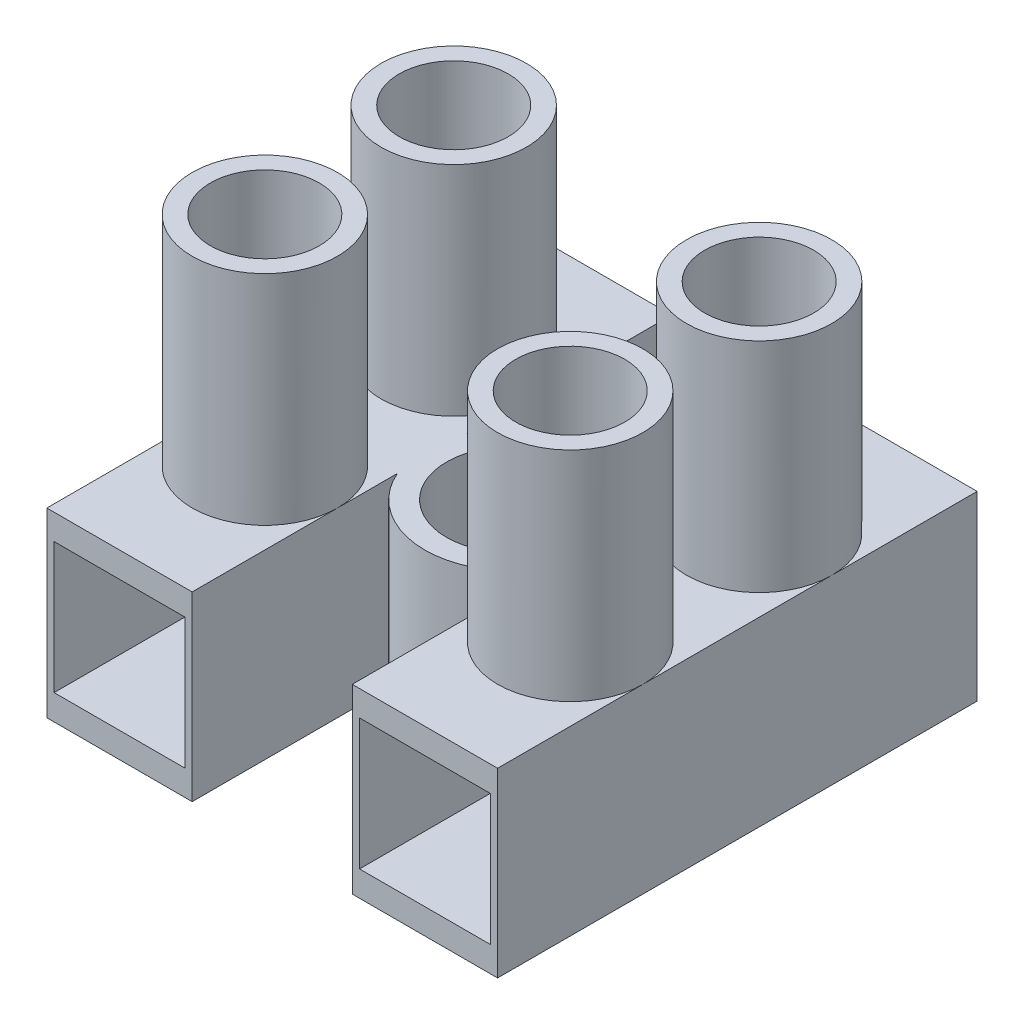
SolidWorks part; units mm, degrees
material "Nylon 6/10"
ref_plane "Front Plane" through (0, 0, 0) normal (0, 0, 1) x (1, 0, 0)
ref_plane "Top Plane" through (0, 0, 0) normal (0, 1, 0) x (1, 0, 0)
ref_plane "Right Plane" through (0, 0, 0) normal (1, 0, 0) x (0, 0, -1)
sketch "Sketch1" plane through (0, 0, 0) normal (0, 1, 0) x (1, 0, 0)
  line L0 (-2.7981, -1.2088) -> (-2.7981, -8.382)
  line L1 (2.7981, 8.382) -> (7.8781, 8.382)
  line L2 (2.7981, 8.382) -> (2.7981, 1.2088)
  line L3 (2.7981, -8.382) -> (7.8781, -8.382)
  line L4 (7.8781, 8.382) -> (7.8781, -8.382)
  line L5 (-7.8781, 8.382) -> (-2.7981, 8.382)
  line L6 (-7.8781, 8.382) -> (-7.8781, -8.382)
  line L7 (-7.8781, -8.382) -> (-2.7981, -8.382)
  line L8 (-2.7981, 8.382) -> (-2.7981, 1.2088)
  line L9 (2.7981, -1.2088) -> (2.7981, -8.382)
  arc A1 (-2.7981, -1.2088) -> (2.7981, -1.2088) centre (0, 0) ccw
  arc A2 (2.7981, 1.2088) -> (-2.7981, 1.2088) centre (0, 0) ccw
  point P12 (-7.8781, 0)
  point P13 (7.8781, 0)
  dimension "D6" = 6.096
  dimension "D1" = 16.764
  dimension "D2" = 5.08
  dimension "D3" = 5.08
  dimension "D4" = 16.764
extrude "Boss-Extrude1" add sketch "Sketch1" against normal blind 6.35
sketch "Sketch2" plane through (0, 0, 0) normal (0, 1, 0) x (1, 0, 0)
  circle A0 centre (0, 0) radius 2.286
  dimension "D1" = 4.572
extrude "Cut-Extrude1" cut sketch "Sketch2" against normal through all
sketch "Sketch3" plane through (0, 0, 8.382) normal (0, 0, 1) x (1, 0, 0)
  line L0 (-7.8781, -6.35) -> (-7.8781, 0) construction
  line L1 (-7.6241, -0.889) -> (-3.0521, -0.889)
  line L2 (-7.6241, -0.889) -> (-7.6241, -5.461)
  line L3 (-7.6241, -5.461) -> (-3.0521, -5.461)
  line L4 (-3.0521, -0.889) -> (-3.0521, -5.461)
  line L5 (3.0521, -0.889) -> (7.6241, -0.889)
  line L6 (3.0521, -0.889) -> (3.0521, -5.461)
  line L7 (3.0521, -5.461) -> (7.6241, -5.461)
  line L8 (7.6241, -0.889) -> (7.6241, -5.461)
  line L9 (-7.8781, 0) -> (-2.7981, 0) construction
  line L10 (2.7981, 0) -> (7.8781, 0) construction
  point P8 (-7.6241, -3.175)
  point P11 (-7.8781, -3.175)
  point P12 (3.0521, -3.175)
  point P15 (-5.3381, 0)
  point P16 (-5.3381, -0.889)
  point P19 (5.3381, 0)
  point P20 (5.3381, -0.889)
  dimension "D1" = 4.572
  dimension "D2" = 4.572
  dimension "D3" = 4.572
  dimension "D4" = 4.572
extrude "Cut-Extrude2" cut sketch "Sketch3" against normal blind 7.62
sketch "Sketch4" plane through (0, 0, -8.382) normal (0, 0, -1) x (-1, 0, 0)
  line L0 (-7.8781, -6.35) -> (-7.8781, 0) construction
  line L1 (-7.6241, -0.889) -> (-3.0521, -0.889)
  line L2 (-7.6241, -0.889) -> (-7.6241, -5.461)
  line L3 (-7.6241, -5.461) -> (-3.0521, -5.461)
  line L4 (-3.0521, -0.889) -> (-3.0521, -5.461)
  line L5 (3.0521, -0.889) -> (7.6241, -0.889)
  line L6 (3.0521, -0.889) -> (3.0521, -5.461)
  line L7 (3.0521, -5.461) -> (7.6241, -5.461)
  line L8 (7.6241, -0.889) -> (7.6241, -5.461)
  line L9 (-7.8781, 0) -> (-2.7981, 0) construction
  line L10 (2.7981, 0) -> (7.8781, 0) construction
  point P10 (-7.8781, -3.175)
  point P11 (-7.6241, -3.175)
  point P12 (3.0521, -3.175)
  point P15 (-5.3381, 0)
  point P16 (-5.3381, -0.889)
  point P19 (5.3381, 0)
  point P20 (5.3381, -0.889)
  dimension "D1" = 4.572
  dimension "D2" = 4.572
  dimension "D3" = 4.572
  dimension "D4" = 4.572
extrude "Cut-Extrude3" cut sketch "Sketch4" against normal blind 7.62
sketch "Sketch5" plane through (0, 0, 0) normal (0, 1, 0) x (1, 0, 0)
  line L0 (7.8781, 8.382) -> (2.7981, 8.382) construction
  line L1 (2.7981, -8.382) -> (7.8781, -8.382) construction
  line L2 (-2.7981, 8.382) -> (-7.8781, 8.382) construction
  circle A0 centre (-5.3381, -3.302) radius 2.54
  circle A1 centre (-5.3381, 3.302) radius 2.54
  circle A2 centre (5.3381, 3.302) radius 2.54
  circle A3 centre (5.3381, -3.302) radius 2.54
  circle A4 centre (-5.3381, 3.302) radius 1.905
  circle A5 centre (5.3381, 3.302) radius 1.905
  circle A6 centre (5.3381, -3.302) radius 1.905
  circle A7 centre (-5.3381, -3.302) radius 1.905
  point P13 (5.3381, 8.382)
  point P16 (-5.3381, 8.382)
  dimension "D1" = 5.08
  dimension "D2" = 5.08
  dimension "D3" = 5.08
  dimension "D4" = 5.08
  dimension "D5" = 5.08
  dimension "D6" = 5.08
  dimension "D7" = 3.81
  dimension "D8" = 3.81
  dimension "D9" = 3.81
  dimension "D10" = 3.81
extrude "Boss-Extrude2" add sketch "Sketch5" along normal blind 7.62
